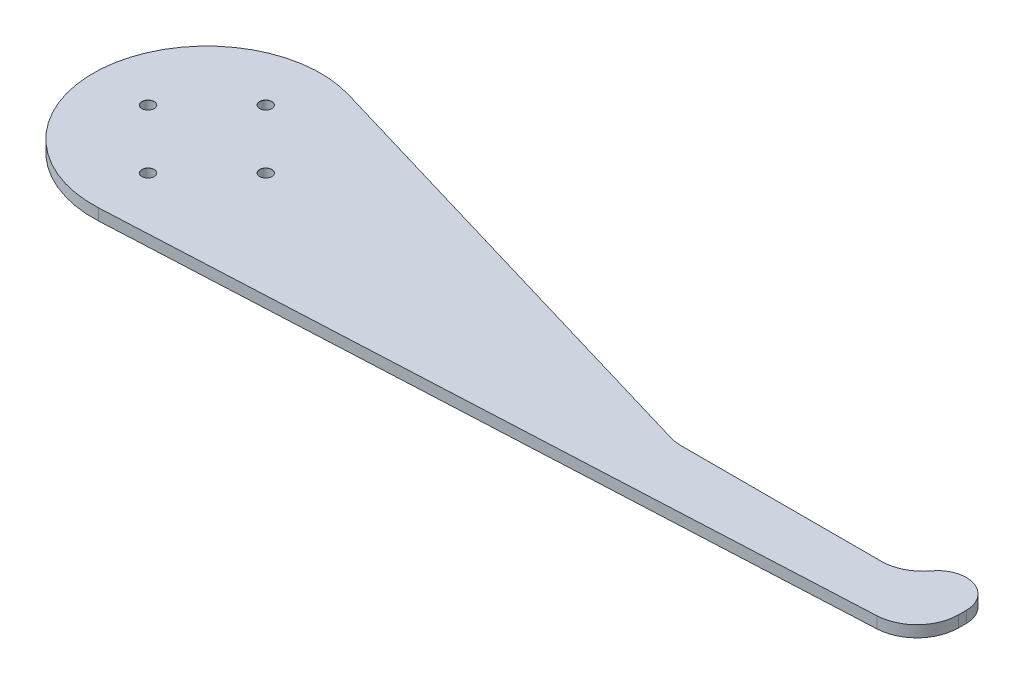
SolidWorks part; units mm, degrees
ref_plane "Front Plane" through (0, 0, 0) normal (0, 0, 1) x (1, 0, 0)
ref_plane "Top Plane" through (0, 0, 0) normal (0, 1, 0) x (1, 0, 0)
ref_plane "Right Plane" through (0, 0, 0) normal (1, 0, 0) x (0, 0, -1)
sketch "Sketch1" plane through (0, 0, 0) normal (0, 1, 0) x (1, 0, 0)
  line L0 (0, 0) -> (200, 0) construction
  line L1 (207.5, -7.5) -> (207.5, -19.9909)
  line L3 (207.5, -19.9909) -> (0, -30.0351)
  line L4 (192.5, -7.5) -> (130.8046, -7.5)
  line L5 (130.8046, -7.5) -> (8.5296, 28.7619)
  circle A0 centre (0, 0) radius 30
  circle A2 centre (200, -7.5) radius 7.5
  point P11 (207.5, -30)
  point P13 (207.5, -30)
  point P14 (130.8046, -7.5)
  point P15 (207.5, -30)
  point P16 (207.5, -19.9909)
  dimension "D1" = 15
  dimension "D3" = 60
  dimension "D2" = 200
extrude "Boss-Extrude1" add sketch "Sketch1" along normal blind 3
hole_wizard "M3 Clearance Hole1" positions "Sketch2" profile "Sketch3" hole size "M3" standard "ANSI Metric" end condition through all
sketch "Sketch2" plane through (0, 3, 0) normal (0, 1, 0) x (1, 0, 0)
  circle A0 centre (0, 0) radius 15.5
  point P5 (0, 15.5)
  point P7 (15.5, 0)
  point P9 (0, -15.5)
  point P11 (-15.5, 0)
sketch "Sketch3" plane through (-15.5, 3, 0) normal (1, 0, 0) x (0, 0, 1)
  line L0 (0, 0) -> (0, 3)
  line L1 (0, 3) -> (1.6, 3)
  line L2 (1.6, 3) -> (1.6, 0.025)
  line L3 (1.6, 0.025) -> (1.625, 0)
  line L5 (1.625, 0) -> (0, 0)
  line L6 (-1.6, 0.025) -> (-1.625, 0) construction
  line L11 (0, -6.35) -> (0, 107.95) construction
  dimension "Thru Hole Dia." = 3.2
  dimension "Thru Hole Depth" = 3
  dimension "Near C'Sink Dia." = 3.25
  dimension "Near C'Sink Angle" = 90
fillet "Fillet2" radius 11 3 edges at (207.5, 1.5, 19.9909) (192.5, 1.5, 7.5) (130.8046, 1.5, 7.5)
